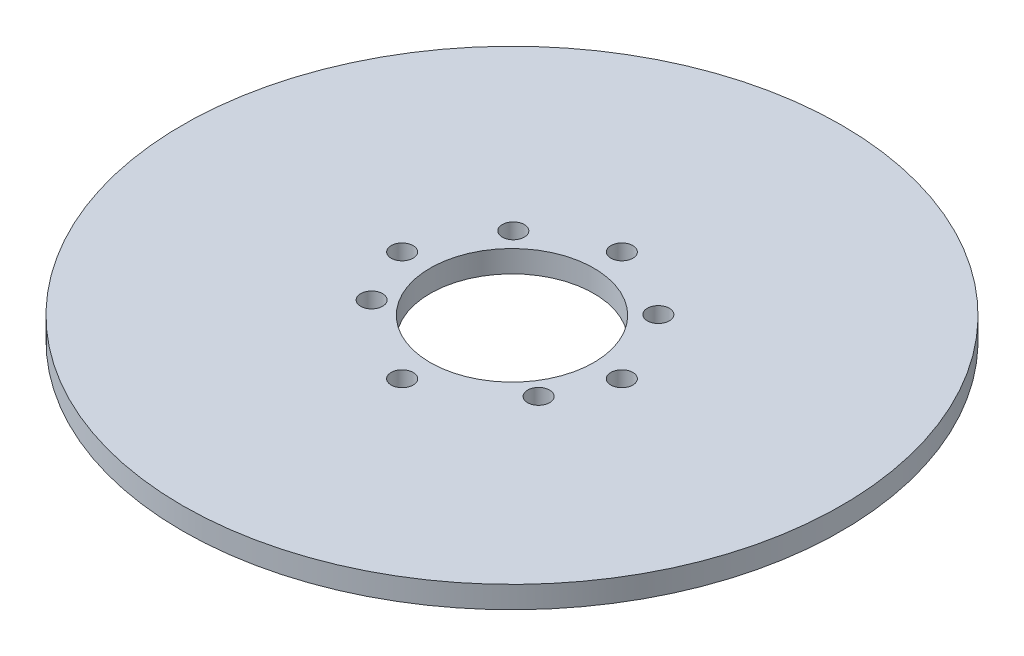
SolidWorks part; units mm, degrees
ref_plane "Front Plane" through (0, 0, 0) normal (0, 0, 1) x (1, 0, 0)
ref_plane "Top Plane" through (0, 0, 0) normal (0, 1, 0) x (1, 0, 0)
ref_plane "Right Plane" through (0, 0, 0) normal (1, 0, 0) x (0, 0, -1)
sketch "Sketch1" plane through (0, 0, 0) normal (0, 1, 0) x (1, 0, 0)
  line L0 (-33, 30.5941) -> (-38, -28.8961) construction
  line L1 (33, 30.5941) -> (38, -28.8961) construction
  line L2 (-33, 30.5941) -> (38, -28.8961) construction
  line L3 (33, 30.5941) -> (-38, -28.8961) construction
  line L4 (-33, 30.5941) -> (33, 30.5941) construction
  line L5 (-33, 30.5941) -> (0, 0) construction
  circle A0 centre (-33, 30.5941) radius 5
  circle A1 centre (33, 30.5941) radius 5
  circle A3 centre (38, -28.8961) radius 5
  circle A4 centre (-38, -28.8961) radius 5
  arc A10 (33.5486, 15.6042) -> (34.2563, 15.6468) centre (33, 30.5941) ccw
  circle A11 centre (0, -3) radius 37.25
  circle A12 centre (0, 47) radius 5
  circle A13 centre (50, -3) radius 5
  circle A14 centre (0, -53) radius 5
  circle A15 centre (-50, -3) radius 5
  circle A16 centre (0, -3) radius 150
  point P2 (0, 30.5941)
  point P25 (0, -3)
  dimension "D4" = 10
  dimension "D1" = 59.7
  dimension "D6" = 3
  dimension "D7" = 50
  dimension "D8" = 10
  dimension "D9" = 4
  dimension "D10" = 300
  dimension "D11" = 74.5
  dimension "D2" = 66
  dimension "D3" = 45
  dimension "D5" = 76
extrude "Boss-Extrude1" add sketch "Sketch1" along normal blind 10
